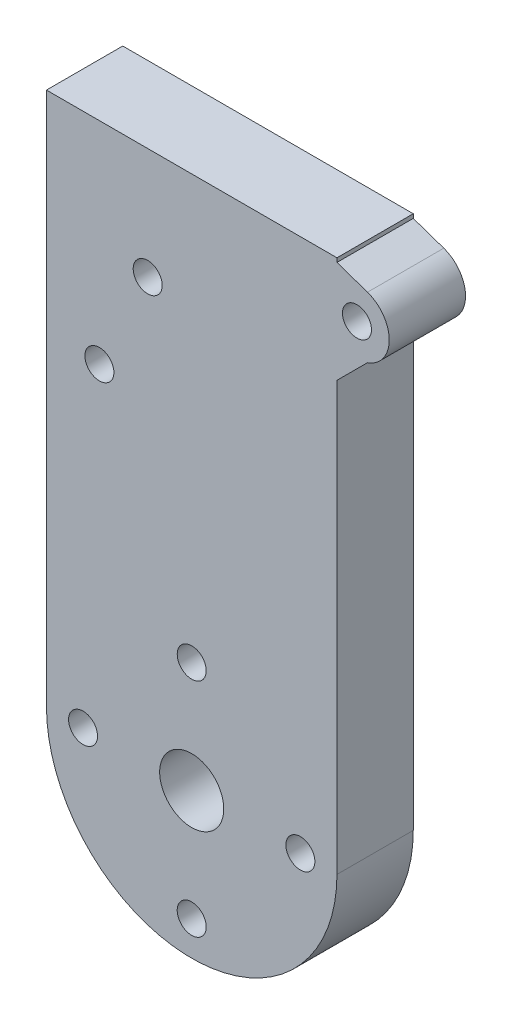
SolidWorks part; units mm, degrees
ref_plane "Front Plane" through (0, 0, 0) normal (1, 0, 0) x (0, 1, 0)
ref_plane "Top Plane" through (0, 0, 0) normal (0, 0, 1) x (0, 1, 0)
ref_plane "Right Plane" through (0, 0, 0) normal (0, 1, 0) x (-1, 0, 0)
sketch "Sketch1" plane through (0, 0, 0) normal (0, 0, 1) x (0, 1, 0)
  line L0 (-30.9944, 0) -> (30.773, 0) construction
  line L1 (0, -25.7549) -> (0, 25.6073) construction
  line L2 (0, 19.0389) -> (70, 19.0389)
  line L3 (0, -19.0389) -> (56.0913, -19.0389)
  line L4 (70, -19.0389) -> (70, 19.0389)
  line L5 (69.4693, -19.0389) -> (68.0913, -23.0389)
  line L6 (69.4693, -19.0389) -> (70, -19.0389)
  line L7 (60.0913, -23.0389) -> (56.0913, -19.0389)
  arc A0 (0, 19.0389) -> (0, -19.0389) centre (0, 0) ccw
  circle A1 centre (0, 14.2427) radius 1.9
  circle A2 centre (0, 0) radius 4.2
  circle A3 centre (0, -14.2427) radius 1.9
  circle A4 centre (-14.5379, 0) radius 1.9
  circle A5 centre (14.5379, 0) radius 1.9
  arc A7 (68.0913, -23.0389) -> (60.0913, -23.0389) centre (64.0913, -21.6609) cw
  circle A8 centre (64.0913, -21.6609) radius 1.9
  circle A9 centre (42.3524, 12.0999) radius 1.9
  circle A10 centre (55.3988, 5.772) radius 1.9
  dimension "D1" = 8.4
  dimension "D2" = 3.8
  dimension "D3" = 3.8
  dimension "D4" = 3.8
  dimension "D5" = 3.8
  dimension "D6" = 3.8
  dimension "D7" = 14.5
  dimension "D8" = 70
extrude "Boss-Extrude1" add sketch "Sketch1" along normal blind 10
sketch "Sketch2" plane through (0, 0, 0) normal (0, 0, -1) x (1, 0, 0)
  circle A0 centre (0, 0) radius 12
  circle A1 centre (0, 0) radius 11.4
  dimension "D1" = 22.8
  dimension "D2" = 24
extrude "Boss-Extrude2" add sketch "Sketch2" along normal blind 7 contours A0
sketch "Sketch3" plane through (0, 0, -7) normal (0, 0, -1) x (1, 0, 0)
  circle A0 centre (0, 0) radius 11.2
  dimension "D1" = 22.4
extrude "Cut-Extrude1" cut sketch "Sketch3" against normal blind 7
sketch "Sketch4" plane through (0, 0, 0) normal (0, 0, -1) x (1, 0, 0)
  circle A0 centre (-12.0999, -42.3524) radius 2.9
  circle A1 centre (-5.772, -55.3988) radius 2.9
  dimension "D1" = 5.8
  dimension "D2" = 5.8
extrude "Cut-Extrude2" cut sketch "Sketch4" against normal blind 2
